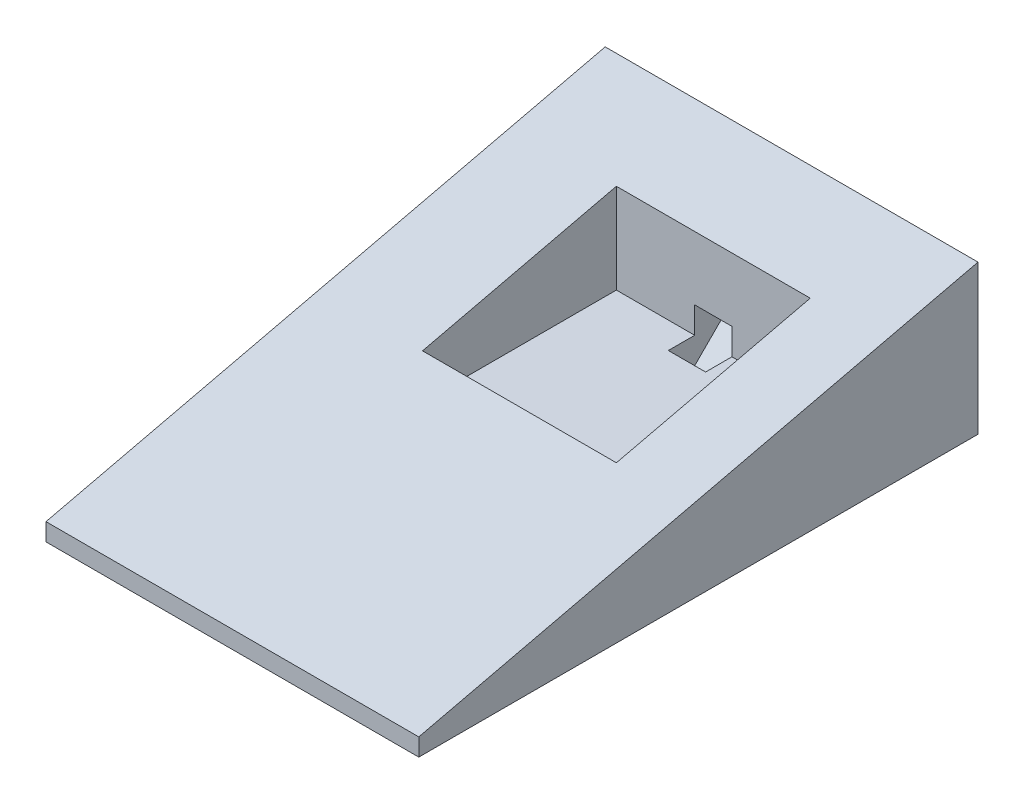
SolidWorks part; units mm, degrees
ref_plane "Front Plane" through (0, 0, 0) normal (0, 0, 1) x (1, 0, 0)
ref_plane "Top Plane" through (0, 0, 0) normal (0, 1, 0) x (1, 0, 0)
ref_plane "Right Plane" through (0, 0, 0) normal (1, 0, 0) x (0, 0, -1)
sketch "Sketch1" plane through (0, 0, 0) normal (0, 1, 0) x (1, 0, 0)
  line L1 (-50, -75) -> (50, -75)
  line L2 (-50, -75) -> (-50, 75)
  line L3 (-50, 75) -> (50, 75)
  line L4 (50, -75) -> (50, 75)
  line L5 (-50, -75) -> (50, 75) construction
  line L6 (-50, 75) -> (50, -75) construction
  point P0 (0, 0)
  dimension "D1" = 150
  dimension "D2" = 100
extrude "Boss-Extrude1" add sketch "Sketch1" along normal blind 40
sketch "Sketch3" plane through (0, 40, 0) normal (0, 1, 0) x (1, 0, 0)
  line L0 (50, 75) -> (-50, 75) construction
  line L1 (-22, -2) -> (30, -2)
  line L2 (-22, -2) -> (-22, 50)
  line L3 (-22, 50) -> (30, 50)
  line L4 (30, -2) -> (30, 50)
  line L5 (-22, -2) -> (30, 50) construction
  line L6 (-22, 50) -> (30, -2) construction
  line L7 (50, -75) -> (50, 75) construction
  point P0 (4, 24)
  dimension "D1" = 52
  dimension "D2" = 52
  dimension "D3" = 25
  dimension "D4" = 20
extrude "Cut-Extrude2" cut sketch "Sketch3" against normal blind 30
sketch "Sketch2" plane through (50, 0, 0) normal (1, 0, 0) x (0, 0, -1)
  line L0 (75, 40) -> (-95, 0)
  line L3 (-75, 40) -> (-75, 0) construction
  line L4 (-95, 0) -> (-95, 40)
  line L5 (-95, 40) -> (75, 40)
  line L6 (-75, 0) -> (75, 0) construction
  dimension "D1" = 20
extrude "Cut-Extrude1" cut sketch "Sketch2" against normal through all
ref_plane "Plane1" through (0, 30, -30) normal (0, -0.7071, 0.7071) x (1, 0, 0)
ref_plane "Plane2" through (0, -20, -20) normal (0, 0.7071, 0.7071) x (-1, 0, 0)
sketch "Sketch4" plane through (0, -20, -20) normal (0, 0.7071, 0.7071) x (-1, 0, 0)
  line L0 (-30, -42.4264) -> (22, -42.4264) construction
  line L1 (-9, -47.4264) -> (1, -47.4264)
  line L2 (-9, -47.4264) -> (-9, -37.4264)
  line L3 (-9, -37.4264) -> (1, -37.4264)
  line L4 (1, -47.4264) -> (1, -37.4264)
  line L5 (-9, -47.4264) -> (1, -37.4264) construction
  line L6 (-9, -37.4264) -> (1, -47.4264) construction
  point P0 (-4, -42.4264)
  dimension "D1" = 10
  dimension "D2" = 10
extrude "Cut-Extrude5" cut sketch "Sketch4" against normal blind 5 and the other way blind 10
